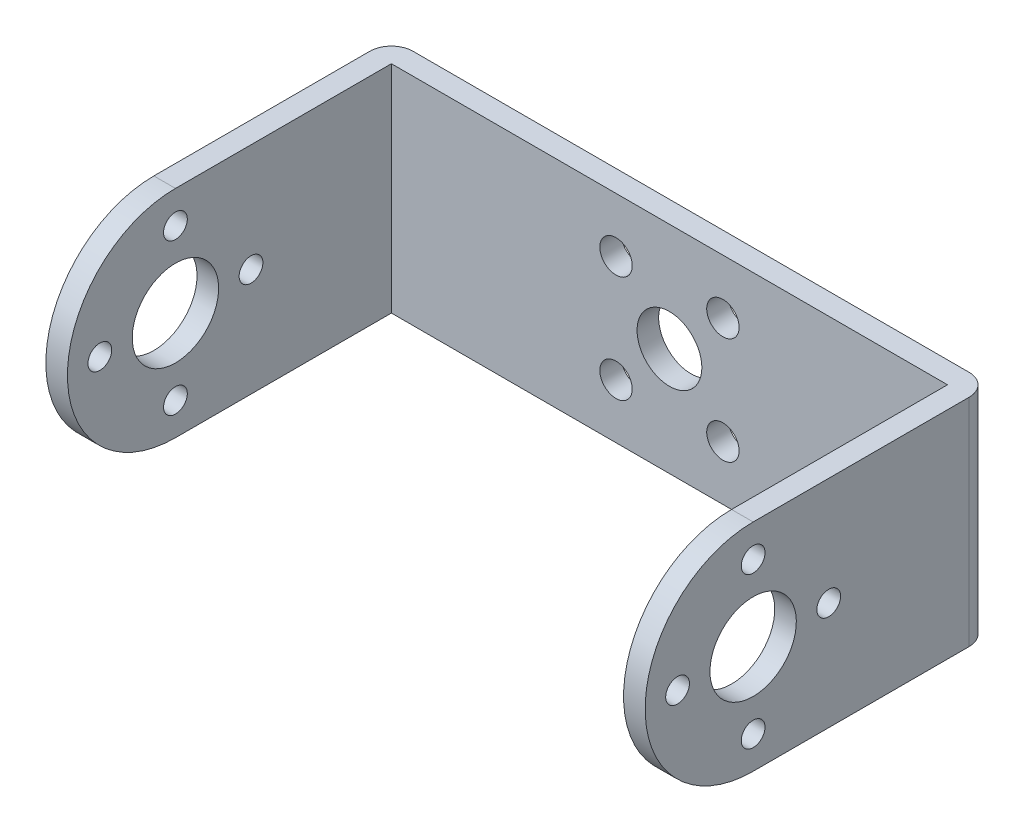
SolidWorks part; units mm, degrees
ref_plane "前视" through (0, 0, 0) normal (0, 0, 1) x (1, 0, 0)
ref_plane "上视" through (0, 0, 0) normal (0, 1, 0) x (1, 0, 0)
ref_plane "右视" through (0, 0, 0) normal (1, 0, 0) x (0, 0, -1)
sketch "草图1" plane through (0, 0, 0) normal (0, 0, 1) x (1, 0, 0)
  line L0 (0, 28.047) -> (0, -23.855) construction
  line L1 (-36.106, 0) -> (28.7266, 0) construction
  line L2 (16, 21.4196) -> (16, -17.867) construction
  line L3 (-27.75, 10) -> (27.75, 10)
  line L4 (-27.75, 10) -> (-27.75, -10)
  line L5 (-27.75, -10) -> (27.75, -10)
  line L6 (27.75, 10) -> (27.75, -10)
  line L7 (-27.75, 10) -> (27.75, -10) construction
  line L8 (-27.75, -10) -> (27.75, 10) construction
  line L9 (-13, 21.4196) -> (-13, -18.4127) construction
  circle A0 centre (0, 0) radius 3
  circle A1 centre (0, 0) radius 7 construction
  circle A2 centre (-4.9497, 4.9497) radius 1.5
  circle A3 centre (4.9497, 4.9497) radius 1.5
  circle A4 centre (4.9497, -4.9497) radius 1.5
  circle A5 centre (-4.9497, -4.9497) radius 1.5
  point P5 (0, 0)
  point P24 (0, 0)
  dimension "D3" = 6
  dimension "D4" = 14
  dimension "D5" = 3
  dimension "D1" = 20
  dimension "D2" = 55.5
  dimension "D7" = 13
  dimension "D8" = 16
  dimension "D6" = 4
extrude "凸台-拉伸1" add sketch "草图1" along normal blind 2
sketch "草图2" plane through (-27.75, 0, 0) normal (-1, 0, 0) x (0, 0, 1)
  line L0 (0, 12.3738) -> (0, -12.327) construction
  line L1 (42.5749, 0) -> (-6.362, 0) construction
  line L2 (2, 10) -> (2, -10) construction
  line L3 (2, 10) -> (2, -10)
  line L4 (2, 10) -> (22, 10)
  line L5 (22, -10) -> (2, -10)
  line L6 (22, 24.8407) -> (22, -19.8469) construction
  arc A0 (22, -10) -> (22, 10) centre (22, 0) ccw
  circle A1 centre (22, 0) radius 7 construction
  circle A2 centre (22, 0) radius 4
  circle A3 centre (29, 0) radius 1.1
  circle A4 centre (22, -7) radius 1.1
  circle A5 centre (15, 0) radius 1.1
  circle A6 centre (22, 7) radius 1.1
  point P25 (22, 0)
  dimension "D1" = 20
  dimension "D3" = 14
  dimension "D4" = 8
  dimension "D5" = 2.2
  dimension "D2" = 20
  dimension "D6" = 4
extrude "凸台-拉伸2" add sketch "草图2" against normal blind 2
mirror "镜向1" about plane through (0, 0, 0) normal (1, 0, 0) of "凸台-拉伸2"
fillet "圆角1" radius 2 2 edges at (-27.75, 0, 0) (27.75, 0, 0)
